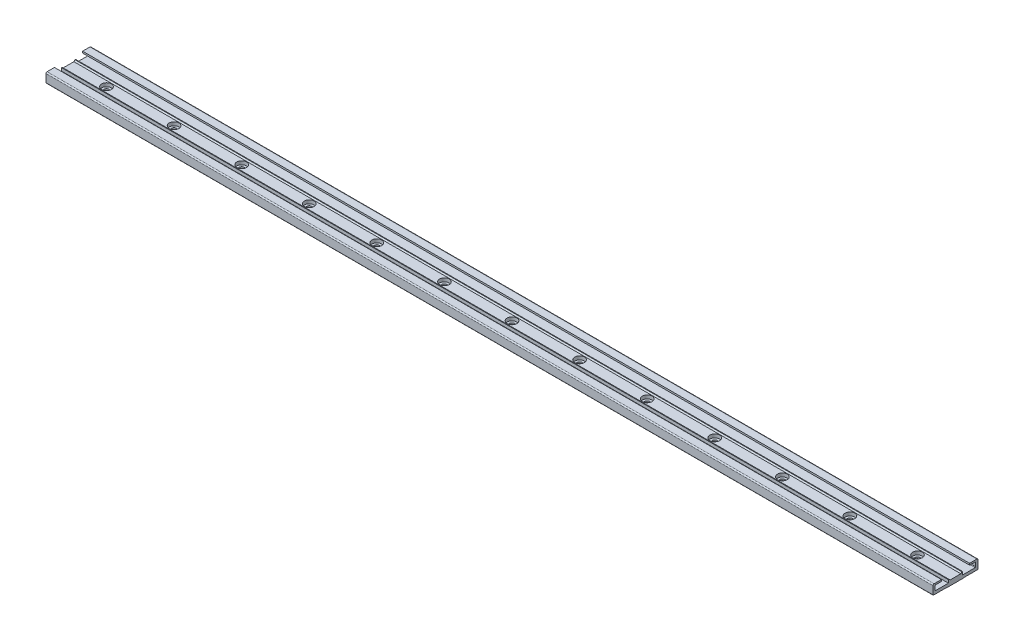
SolidWorks part; units mm, degrees
material "6061-T6 (SS)"
ref_plane "Front" through (0, 0, 0) normal (0, 0, 1) x (1, 0, 0)
ref_plane "Top" through (0, 0, 0) normal (0, 1, 0) x (1, 0, 0)
ref_plane "Right" through (0, 0, 0) normal (1, 0, 0) x (0, 0, -1)
sketch "Sketch1" plane through (0, 0, 0) normal (1, 0, 0) x (0, 0, -1)
  line L0 (-8, 0.2) -> (-8, 0)
  line L1 (-8, 0) -> (8, 0)
  line L2 (8, 0) -> (8, 0.2)
  line L3 (8, 0.2) -> (19.5, 0.2)
  line L4 (20, 0.7) -> (20, 7.7)
  line L5 (19, 8.7) -> (12.5, 8.7)
  line L6 (12.5, 8.7) -> (12.5, 7.2)
  line L7 (12.5, 7.2) -> (17.5, 7.2)
  line L8 (18, 6.7) -> (18, 3.3)
  line L9 (17.5, 2.8) -> (6.3, 2.8)
  line L10 (6.3, 2.8) -> (6.3, 5.5)
  line L11 (6.3, 5.5) -> (5.75, 5.5)
  line L12 (5.75, 5.5) -> (4.75, 4.5)
  line L13 (4.75, 4.5) -> (-4.75, 4.5)
  line L14 (-4.75, 4.5) -> (-5.75, 5.5)
  line L15 (-5.75, 5.5) -> (-6.3, 5.5)
  line L16 (-6.3, 5.5) -> (-6.3, 2.8)
  line L17 (-6.3, 2.8) -> (-17.5, 2.8)
  line L18 (-18, 3.3) -> (-18, 6.7)
  line L19 (-17.5, 7.2) -> (-12.5, 7.2)
  line L20 (-12.5, 7.2) -> (-12.5, 8.7)
  line L21 (-12.5, 8.7) -> (-19, 8.7)
  line L22 (-20, 7.7) -> (-20, 0.7)
  line L23 (-19.5, 0.2) -> (-8, 0.2)
  arc A0 (19.5, 0.2) -> (20, 0.7) centre (19.5, 0.7) ccw
  arc A1 (20, 7.7) -> (19, 8.7) centre (19, 7.7) ccw
  arc A2 (18, 6.7) -> (17.5, 7.2) centre (17.5, 6.7) ccw
  arc A3 (17.5, 2.8) -> (18, 3.3) centre (17.5, 3.3) ccw
  arc A4 (-18, 3.3) -> (-17.5, 2.8) centre (-17.5, 3.3) ccw
  arc A5 (-17.5, 7.2) -> (-18, 6.7) centre (-17.5, 6.7) ccw
  arc A6 (-19, 8.7) -> (-20, 7.7) centre (-19, 7.7) ccw
  arc A7 (-20, 0.7) -> (-19.5, 0.2) centre (-19.5, 0.7) ccw
extrude "Boss-Extrude1" add sketch "Sketch1" along normal blind 787.4
hole_wizard "CBORE for M4 SBHCS1" positions "Sketch2" profile "Sketch3" counterbore size "M4" standard "ANSI Metric" end condition through all
sketch "Sketch2" plane through (0, 4.5, 0) normal (0, 1, 0) x (1, 0, 0)
  line L1 (33.7, 0) -> (0, 0) construction
  line L3 (787.4, 0) -> (753.7, 0) construction
  line L4 (787.4, 4.75) -> (787.4, -4.75) construction
  point P0 (33.7, 0)
  dimension "D1" = 720
sketch "Sketch3" plane through (33.7, 4.5, 0) normal (1, 0, 0) x (0, 0, 1)
  line L0 (0, 0) -> (0, 4.5)
  line L1 (0, 4.5) -> (2.25, 4.5)
  line L3 (2.25, 4.5) -> (2.25, 3.1)
  line L4 (2.25, 3.1) -> (4.3, 3.1)
  line L5 (4.3, 3.1) -> (4.3, 0)
  line L7 (4.3, 0) -> (0, 0)
  line L11 (0, -6.35) -> (0, 107.95) construction
  dimension "Thru Hole Dia." = 4.5
  dimension "Thru Hole Depth" = 4.5
  dimension "C'Bore Dia." = 8.6
  dimension "C'Bore Depth" = 3.1
pattern_linear "LPattern1" count 13 spacing 60 along (1, 0, 0) of "CBORE for M4 SBHCS1"
equation "\"END\"= int ( \"RD1@Annotations\" / 60 )"
equation "\"D1@Sketch2\"=(\"END\"-1)*60"
